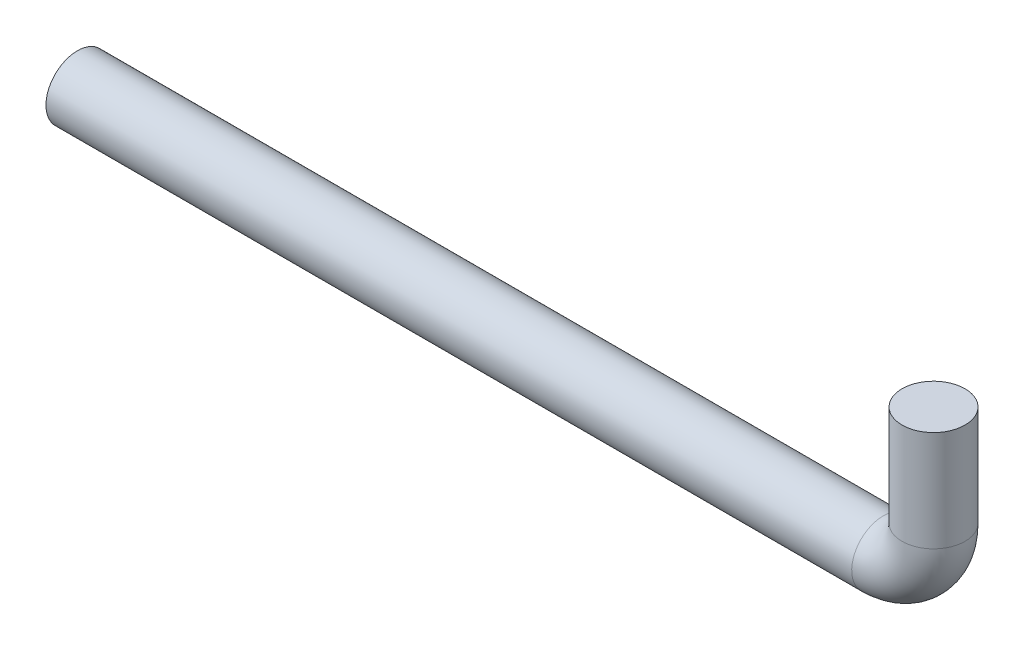
SolidWorks part; units mm, degrees
ref_plane "Front Plane" through (0, 0, 0) normal (0, 0, 1) x (1, 0, 0)
ref_plane "Top Plane" through (0, 0, 0) normal (0, 1, 0) x (1, 0, 0)
ref_plane "Right Plane" through (0, 0, 0) normal (1, 0, 0) x (0, 0, -1)
sketch "Sketch2" plane through (0, 0, 0) normal (0, 0, 1) x (1, 0, 0)
  line L0 (0, 0) -> (20.32, 0)
  line L1 (21.59, 1.27) -> (21.59, 3.81)
  arc A0 (20.32, 0) -> (21.59, 1.27) centre (20.32, 1.27) ccw
  dimension "D3" = 1.27
  dimension "D1" = 2.54
  dimension "D2" = 20.32
sketch "Sketch1" plane through (0, 0, 0) normal (1, 0, 0) x (0, 0, -1)
  circle A0 centre (0, 0) radius 0.7937
  dimension "D1" = 1.5875
sweep "Sweep1" add profiles "Sketch1" path "Sketch2"
